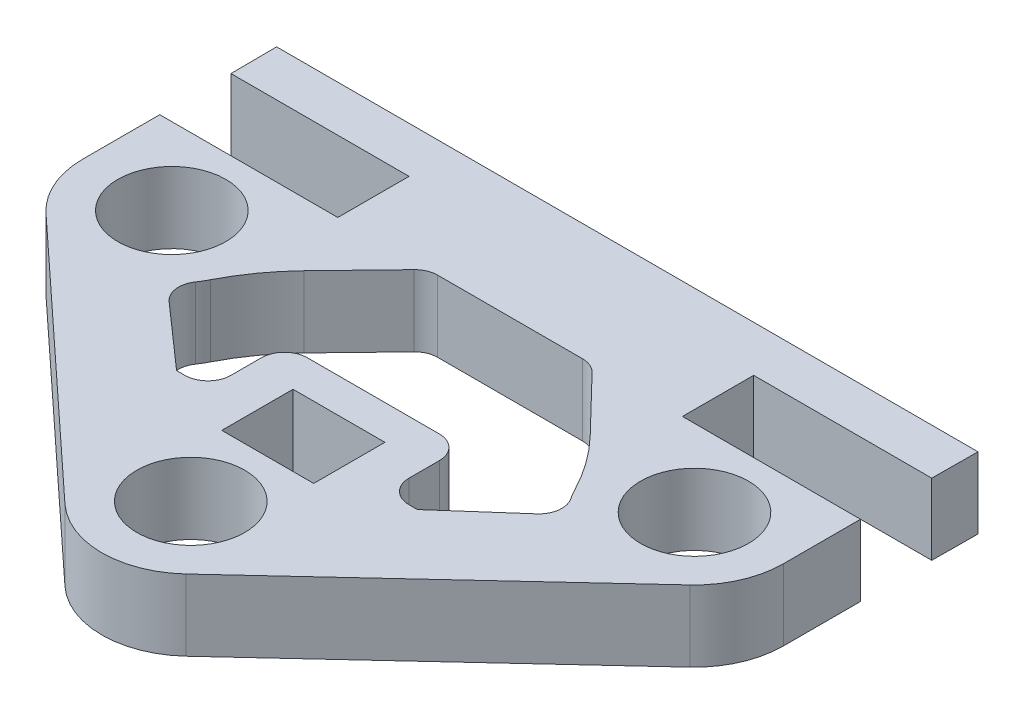
SolidWorks part; units mm, degrees
ref_plane "Front Plane" through (0, 0, 0) normal (0, 0, 1) x (1, 0, 0)
ref_plane "Top Plane" through (0, 0, 0) normal (0, 1, 0) x (1, 0, 0)
ref_plane "Right Plane" through (0, 0, 0) normal (1, 0, 0) x (0, 0, -1)
sketch "Sketch1" plane through (0, 0, 0) normal (0, 1, 0) x (1, 0, 0)
  line L0 (-41.0132, 29.4085) -> (-41.0132, 26.0585)
  line L1 (-41.0132, 32.5085) -> (-41.0274, 34.5085)
  line L2 (-41.0274, 34.5085) -> (-10.4989, 34.5085)
  line L3 (-33.2632, 29.4085) -> (-41.0132, 29.4085) construction
  line L4 (-10.4989, 34.5085) -> (-10.5132, 32.5085)
  line L5 (-33.7675, 22.5686) -> (-31.0029, 20.1301)
  line L6 (-17.7588, 22.5686) -> (-20.5234, 20.1301)
  line L7 (-18.2632, 29.4085) -> (-10.5132, 29.4085) construction
  line L8 (-33.2632, 32.5085) -> (-33.2632, 29.4085)
  line L9 (-18.2632, 32.5085) -> (-18.2632, 29.4085)
  line L10 (-28.9171, 29.4085) -> (-22.6092, 29.4085)
  line L11 (-27.7632, 21.9585) -> (-23.7632, 21.9585)
  line L12 (-37.1382, 28.4085) -> (-37.1382, 29.4085) construction
  line L13 (-10.5132, 29.4085) -> (-10.5132, 26.0585)
  line L14 (-27.7632, 21.9585) -> (-27.7632, 18.8585)
  line L15 (-11.7531, 23.2174) -> (-23.1281, 12.6674)
  line L16 (-39.7732, 23.2174) -> (-28.3982, 12.6674)
  line L17 (-41.0132, 32.5085) -> (-33.2632, 32.5085)
  line L18 (-27.7632, 18.8585) -> (-23.7632, 18.8585)
  line L19 (-41.0132, 29.4085) -> (-33.2632, 29.4085)
  line L20 (-23.7632, 21.9585) -> (-23.7632, 18.8585)
  line L21 (-18.2632, 32.5085) -> (-10.5132, 32.5085)
  line L22 (-25.7632, 17.8585) -> (-25.7632, 18.8585) construction
  line L23 (-18.2632, 29.4085) -> (-10.5132, 29.4085)
  line L24 (-31.0029, 20.1301) -> (-30.6382, 20.1301)
  line L25 (-28.6382, 23.4585) -> (-22.8892, 23.4585)
  line L27 (-31.9863, 26.6707) -> (-29.6363, 29.1033)
  line L28 (-21.8892, 22.4593) -> (-21.8882, 21.1301)
  line L30 (-21.8882, 18.8585) -> (-21.8882, 21.9585) construction
  line L31 (-21.89, 29.1033) -> (-19.54, 26.6707)
  line L32 (-20.8882, 20.1301) -> (-20.5234, 20.1301)
  line L33 (-29.6382, 18.8585) -> (-29.6382, 21.9585) construction
  line L34 (-29.6382, 21.1301) -> (-29.6382, 22.4585)
  circle A0 centre (-14.3882, 26.0585) radius 2.35
  circle A1 centre (-37.1382, 26.0585) radius 2.35
  circle A2 centre (-25.7632, 15.5085) radius 2.35
  arc A3 (-11.7531, 23.2174) -> (-10.5132, 26.0585) centre (-14.3882, 26.0585) ccw
  arc A4 (-39.7732, 23.2174) -> (-41.0132, 26.0585) centre (-37.1382, 26.0585) cw
  arc A5 (-28.3982, 12.6674) -> (-23.1281, 12.6674) centre (-25.7632, 15.5085) ccw
  arc A6 (-33.9331, 23.8806) -> (-33.6907, 24.2891) centre (-37.1382, 26.0585) ccw
  arc A7 (-17.5932, 23.8806) -> (-17.8356, 24.2891) centre (-14.3882, 26.0585) cw
  arc A8 (-21.8882, 21.1301) -> (-20.8882, 20.1301) centre (-20.8882, 21.1301) ccw
  arc A9 (-33.6907, 24.2891) -> (-31.9863, 26.6707) centre (-24.7942, 19.7228) cw
  arc A10 (-33.9331, 23.8806) -> (-33.7675, 22.5686) centre (-33.106, 23.3185) ccw
  arc A11 (-29.6382, 21.1301) -> (-30.6382, 20.1301) centre (-30.6382, 21.1301) cw
  arc A12 (-28.6382, 23.4585) -> (-29.6382, 22.4585) centre (-28.6382, 22.4585) ccw
  arc A13 (-17.5932, 23.8806) -> (-17.7588, 22.5686) centre (-18.4203, 23.3185) cw
  arc A14 (-17.8356, 24.2891) -> (-19.54, 26.6707) centre (-26.7322, 19.7228) ccw
  arc A15 (-22.8892, 23.4585) -> (-21.8892, 22.4593) centre (-22.8892, 22.4585) cw
  arc A16 (-28.9171, 29.4085) -> (-29.6363, 29.1033) centre (-28.9171, 28.4085) ccw
  arc A17 (-22.6092, 29.4085) -> (-21.89, 29.1033) centre (-22.6092, 28.4085) cw
  point P31 (-33.2632, 26.0585)
  point P34 (-34.5031, 23.2174)
  point P40 (-17.0232, 23.2174)
  point P43 (-18.2632, 26.0585)
  point P50 (-22.1849, 18.6647)
  point P66 (-21.8882, 20.1301)
  point P71 (-29.6382, 20.1301)
  dimension "D6" = 10
  dimension "D7" = 4.7
  dimension "D8" = 4.7
  dimension "D9" = 15.5143
  dimension "D11" = 1
  dimension "D12" = 3.875
  dimension "D14" = 1
  dimension "D16" = 1
  dimension "D2" = 2
  dimension "D3" = 3.1
  dimension "D4" = 3.1
  dimension "D5" = 15
  dimension "D10" = 5.9017
  dimension "D13" = 4
  dimension "D15" = 1
extrude "Extrude1" add sketch "Sketch1" along normal blind 3.1
